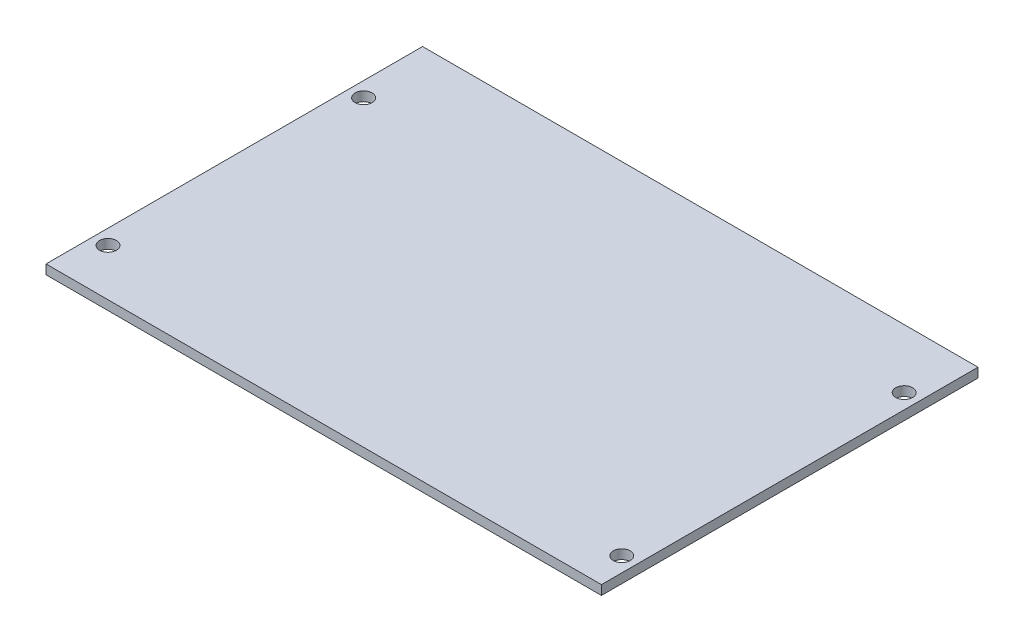
SolidWorks part; units mm, degrees
ref_plane "Ebene vorne" through (0, 0, 0) normal (0, 0, 1) x (1, 0, 0)
ref_plane "Ebene oben" through (0, 0, 0) normal (0, 1, 0) x (1, 0, 0)
ref_plane "Ebene rechts" through (0, 0, 0) normal (1, 0, 0) x (0, 0, -1)
sketch "Sketch1" plane through (0, 0, 0) normal (0, 1, 0) x (1, 0, 0)
  line L1 (-88.5, -60) -> (88.5, -60)
  line L2 (-88.5, -60) -> (-88.5, 60)
  line L3 (-88.5, 60) -> (88.5, 60)
  line L4 (88.5, -60) -> (88.5, 60)
  line L5 (-88.5, -60) -> (88.5, 60) construction
  line L6 (-88.5, 60) -> (88.5, -60) construction
  circle A0 centre (-83.75, 36.4545) radius 2.7
  circle A1 centre (83.75, 41.2222) radius 2.7
  circle A2 centre (83.75, -48.7778) radius 2.7
  circle A3 centre (-83.75, -45) radius 2.7
  point P0 (0, 0)
  point P14 (0, 0)
  point P16 (65.5863, 46.6769)
  dimension "D3" = 90
  dimension "D8" = 5.4
  dimension "D1" = 177
  dimension "D2" = 120
  dimension "D4" = 167.5
  dimension "D5" = 167.5
  dimension "D6" = 4.75
  dimension "D7" = 15
extrude "Extrude1" add sketch "Sketch1" along normal blind 3
